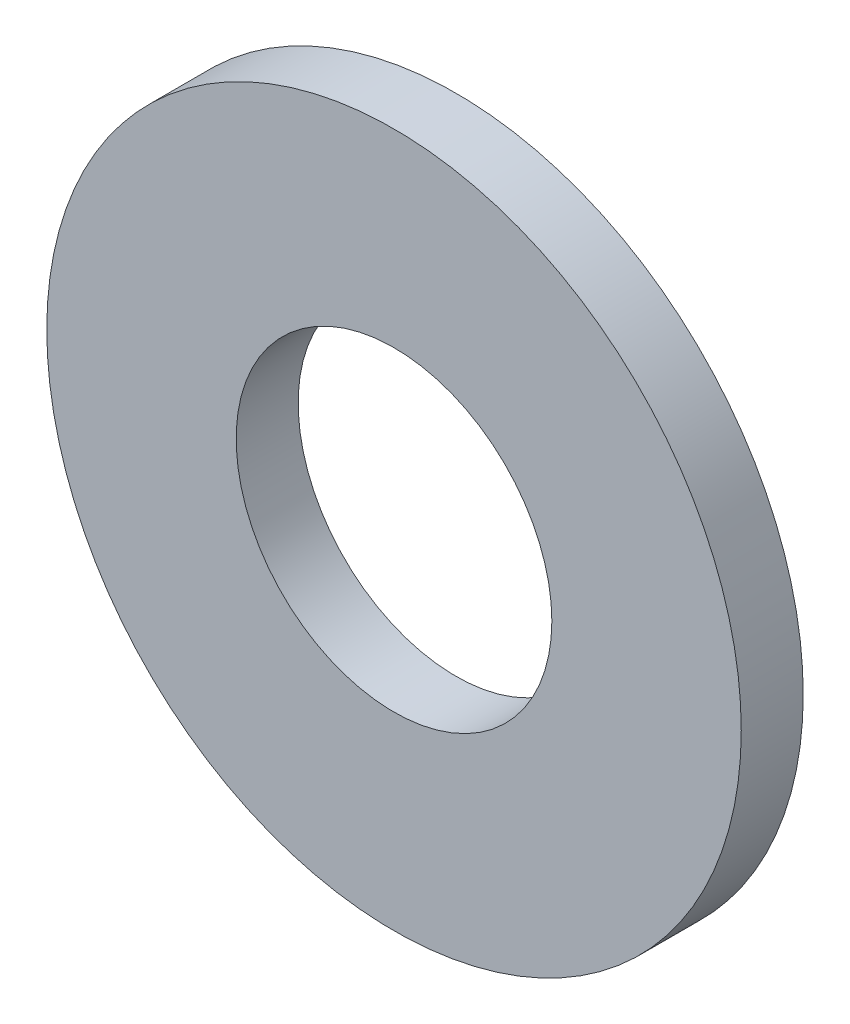
SolidWorks part; units mm, degrees
material "NEOPRENE"
ref_plane "Front Plane" through (0, 0, 0) normal (0, 0, 1) x (1, 0, 0)
ref_plane "Top Plane" through (0, 0, 0) normal (0, 1, 0) x (1, 0, 0)
ref_plane "Right Plane" through (0, 0, 0) normal (1, 0, 0) x (0, 0, -1)
sketch "Sketch1" plane through (0, 0, 0) normal (0, 0, 1) x (1, 0, 0)
  circle A0 centre (0, 0) radius 26.543
  circle A1 centre (0, 0) radius 12.065
extrude "Boss-Extrude1" add sketch "Sketch1" along normal blind 4.7371 contours A0 | A1
